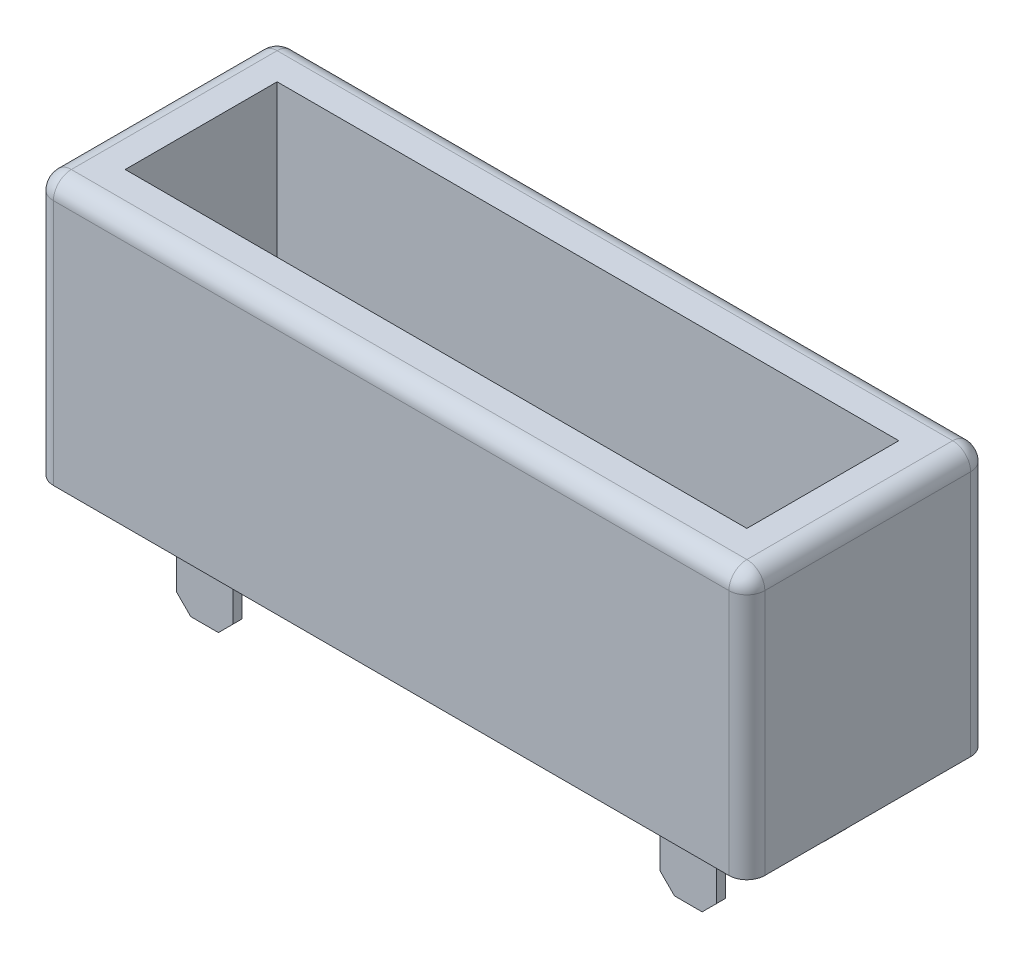
SolidWorks part; units mm, degrees
ref_plane "Front Plane" through (0, 0, 0) normal (0, 0, 1) x (1, 0, 0)
ref_plane "Top Plane" through (0, 0, 0) normal (0, 1, 0) x (1, 0, 0)
ref_plane "Right Plane" through (0, 0, 0) normal (1, 0, 0) x (0, 0, -1)
sketch "Sketch1" plane through (0, 0, 0) normal (0, 1, 0) x (1, 0, 0)
  line L1 (0, 0) -> (19.81, 0)
  line L2 (0, 0) -> (0, 6.73)
  line L3 (0, 6.73) -> (19.81, 6.73)
  line L4 (19.81, 0) -> (19.81, 6.73)
  dimension "D1" = 6.73
  dimension "D2" = 19.81
extrude "Boss-Extrude1" add sketch "Sketch1" along normal blind 7.37
sketch "Sketch2" plane through (0, 0, 0) normal (0, -1, 0) x (1, 0, 0)
  line L0 (9.905, -5.065) -> (9.905, -6.73) construction
  line L1 (3.17, -5.065) -> (16.64, -5.065) construction
  line L2 (3.17, -5.065) -> (3.17, -1.665) construction
  line L3 (3.17, -1.665) -> (16.64, -1.665) construction
  line L4 (16.64, -5.065) -> (16.64, -1.665) construction
  line L5 (19.81, -6.73) -> (0, -6.73) construction
  line L6 (9.905, -1.665) -> (9.905, 0) construction
  line L7 (0, 0) -> (19.81, 0) construction
  line L8 (3.17, -3.365) -> (0, -3.365) construction
  line L9 (0, -6.73) -> (0, 0) construction
  line L10 (16.64, -3.365) -> (19.81, -3.365) construction
  line L11 (19.81, 0) -> (19.81, -6.73) construction
  line L13 (2.385, -5.19) -> (3.955, -5.19)
  line L14 (2.385, -5.19) -> (2.385, -4.94)
  line L15 (2.385, -4.94) -> (3.955, -4.94)
  line L16 (3.955, -5.19) -> (3.955, -4.94)
  line L17 (2.385, -5.19) -> (3.955, -4.94) construction
  line L18 (2.385, -4.94) -> (3.955, -5.19) construction
  line L19 (2.385, -1.79) -> (3.955, -1.79)
  line L20 (2.385, -1.79) -> (2.385, -1.54)
  line L21 (2.385, -1.54) -> (3.955, -1.54)
  line L22 (3.955, -1.79) -> (3.955, -1.54)
  line L23 (2.385, -1.79) -> (3.955, -1.54) construction
  line L24 (2.385, -1.54) -> (3.955, -1.79) construction
  line L25 (15.855, -1.79) -> (17.425, -1.79)
  line L26 (15.855, -1.79) -> (15.855, -1.54)
  line L27 (15.855, -1.54) -> (17.425, -1.54)
  line L28 (17.425, -1.79) -> (17.425, -1.54)
  line L29 (15.855, -1.79) -> (17.425, -1.54) construction
  line L30 (15.855, -1.54) -> (17.425, -1.79) construction
  line L31 (15.855, -5.19) -> (17.425, -5.19)
  line L32 (15.855, -5.19) -> (15.855, -4.94)
  line L33 (15.855, -4.94) -> (17.425, -4.94)
  line L34 (17.425, -5.19) -> (17.425, -4.94)
  line L35 (15.855, -5.19) -> (17.425, -4.94) construction
  line L36 (15.855, -4.94) -> (17.425, -5.19) construction
  dimension "D1" = 3.4
  dimension "D2" = 13.47
  dimension "D3" = 1.57
  dimension "D4" = 0.25
extrude "Boss-Extrude2" add sketch "Sketch2" along normal blind 2.79
chamfer "Chamfer1" distance 0.4 angle 45 8 edges at (17.425, -2.79, -5.065) (15.855, -2.79, -5.065) (17.425, -2.79, -1.665) (15.855, -2.79, -1.665) (3.955, -2.79, -5.065) (2.385, -2.79, -5.065) (3.955, -2.79, -1.665) (2.385, -2.79, -1.665)
sketch "Sketch3" plane through (0, 7.37, 0) normal (0, 1, 0) x (1, 0, 0)
  line L0 (9.905, 6.73) -> (9.905, 3.365) construction
  line L1 (1.25, 1.25) -> (18.56, 1.25)
  line L2 (1.25, 1.25) -> (1.25, 5.48)
  line L3 (1.25, 5.48) -> (18.56, 5.48)
  line L4 (18.56, 1.25) -> (18.56, 5.48)
  line L5 (1.25, 1.25) -> (18.56, 5.48) construction
  line L6 (1.25, 5.48) -> (18.56, 1.25) construction
  line L7 (19.81, 6.73) -> (0, 6.73) construction
  line L8 (9.905, 3.365) -> (9.905, 0) construction
  line L9 (0, 0) -> (19.81, 0) construction
  line L10 (0, 6.73) -> (0, 0) construction
  point P0 (9.905, 3.365)
  dimension "D1" = 1.25
  dimension "D2" = 1.25
extrude "Cut-Extrude1" cut sketch "Sketch3" against normal blind 6
fillet "Fillet1" radius 0.5 8 edges at (19.81, 7.37, -3.365) (9.905, 7.37, -6.73) (9.905, 7.37, 0) (0, 7.37, -3.365) (0, 3.685, -6.73) (0, 3.685, 0) (19.81, 3.685, -6.73) (19.81, 3.685, 0)
